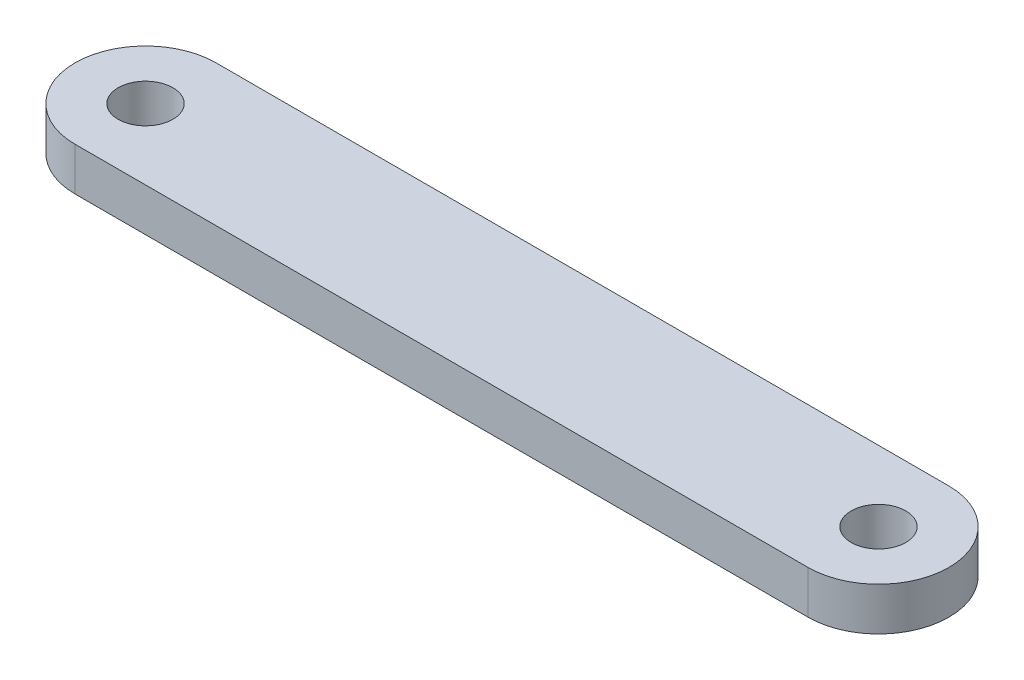
SolidWorks part; units mm, degrees
ref_plane "Front Plane" through (0, 0, 0) normal (0, 0, 1) x (1, 0, 0)
ref_plane "Top Plane" through (0, 0, 0) normal (0, 1, 0) x (1, 0, 0)
ref_plane "Right Plane" through (0, 0, 0) normal (1, 0, 0) x (0, 0, -1)
ref_plane "Plane1" through (0, 5, 0) normal (0, 1, 0) x (1, 0, 0)
sketch "Sketch1" plane through (0, 5, 0) normal (0, 1, 0) x (1, 0, 0)
  line L0 (-95.1125, 3.9335) -> (-10.1125, 3.9335)
  line L1 (-10.1125, 20.2835) -> (-95.1125, 20.2835)
  arc A0 (-95.1125, 20.2835) -> (-95.1125, 3.9335) centre (-95.1125, 12.1085) ccw
  arc A1 (-10.1125, 3.9335) -> (-10.1125, 20.2835) centre (-10.1125, 12.1085) ccw
  circle A2 centre (-95.1125, 12.1085) radius 3.175
  circle A3 centre (-10.1125, 12.1085) radius 3.175
extrude "Boss-Extrude1" add sketch "Sketch1" against normal blind 5
